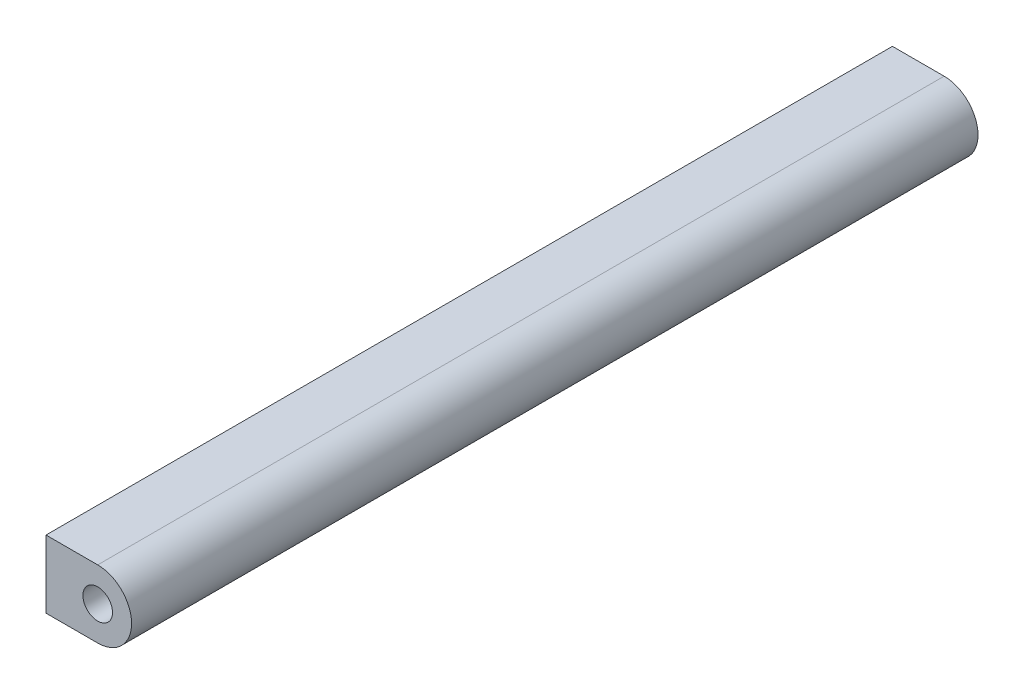
SolidWorks part; units mm, degrees
material "2014 Alloy"
ref_plane "Front Plane" through (0, 0, 0) normal (0, 0, 1) x (1, 0, 0)
ref_plane "Top Plane" through (0, 0, 0) normal (0, 1, 0) x (1, 0, 0)
ref_plane "Right Plane" through (0, 0, 0) normal (1, 0, 0) x (0, 0, -1)
sketch "Sketch1" plane through (0, 0, 0) normal (0, 0, 1) x (1, 0, 0)
  line L0 (0, 40) -> (-61.094, 40)
  line L1 (-61.094, 40) -> (-61.094, -40)
  line L2 (-61.094, -40) -> (0, -40)
  circle A0 centre (0, 0) radius 17.5
  arc A1 (0, 40) -> (0, -40) centre (0, 0) cw
  dimension "D1" = 35
  dimension "50" = 40
extrude "Boss-Extrude1" add sketch "Sketch1" along normal mid plane 1000
sketch "Sketch2" plane through (-61.094, 0, 0) normal (-1, 0, 0) x (0, 0, 1)
  circle A0 centre (0, 0) radius 22.5
  dimension "D1" = 45
extrude "Cut-Extrude1" cut sketch "Sketch2" against normal blind 30
